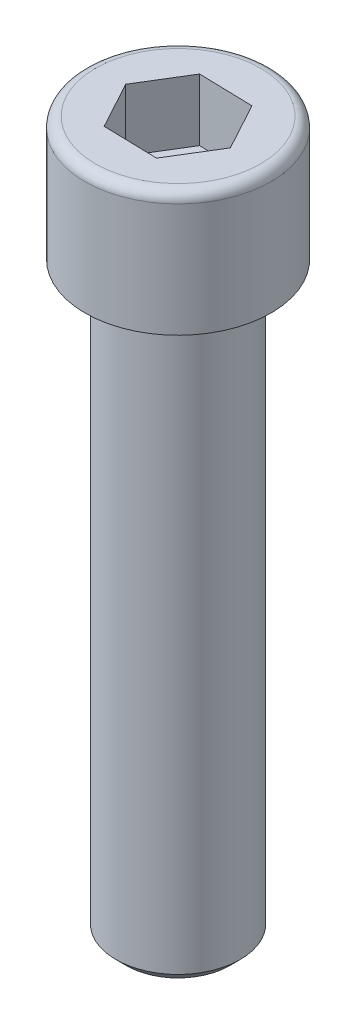
SolidWorks part; units mm, degrees
material "Acier allié"
ref_plane "Plan de face" through (0, 0, 0) normal (0, 0, 1) x (1, 0, 0)
ref_plane "Plan de dessus" through (0, 0, 0) normal (0, 1, 0) x (1, 0, 0)
ref_plane "Plan de droite" through (0, 0, 0) normal (1, 0, 0) x (0, 0, -1)
sketch "DIAMETRE_TETE" plane through (0, 0, 0) normal (0, 1, 0) x (1, 0, 0)
  circle A0 centre (0, 0) radius 27
  dimension "D1" = 54
extrude "HAUTEUR_TETE" add sketch "DIAMETRE_TETE" along normal blind 36
fillet "CONGE" radius 3 1 edges at (0, 36, 27)
sketch "DIAMETRE" plane through (0, 0, 0) normal (0, -1, 0) x (1, 0, 0)
  circle A0 centre (0, 0) radius 18
  dimension "D1" = 36
extrude "LONGUEUR" add sketch "DIAMETRE" along normal blind 170
cosmetic thread "LONGUEUR_FILETAGE" parameters "HAUTEUR_FILETAGE"=84, "D2"=1.202
sketch "LARGEUR_6PANS" plane through (0, 36, 0) normal (0, 1, 0) x (1, 0, 0)
  line L1 (8.1427, 13.2927) -> (-7.4405, 13.6981)
  line L2 (-7.4405, 13.6981) -> (-15.5832, 0.4054)
  line L3 (-15.5832, 0.4054) -> (-8.1427, -13.2927)
  line L4 (-8.1427, -13.2927) -> (7.4405, -13.6981)
  line L5 (7.4405, -13.6981) -> (15.5832, -0.4054)
  line L6 (15.5832, -0.4054) -> (8.1427, 13.2927)
  circle A0 centre (0, 0) radius 13.5 construction
  dimension "D1" = 27
extrude "HAUTEUR_6PANS" cut sketch "LARGEUR_6PANS" against normal blind 18
chamfer "CHANFREIN" distance 3 angle 45 1 edges at (0, -170, -18)
